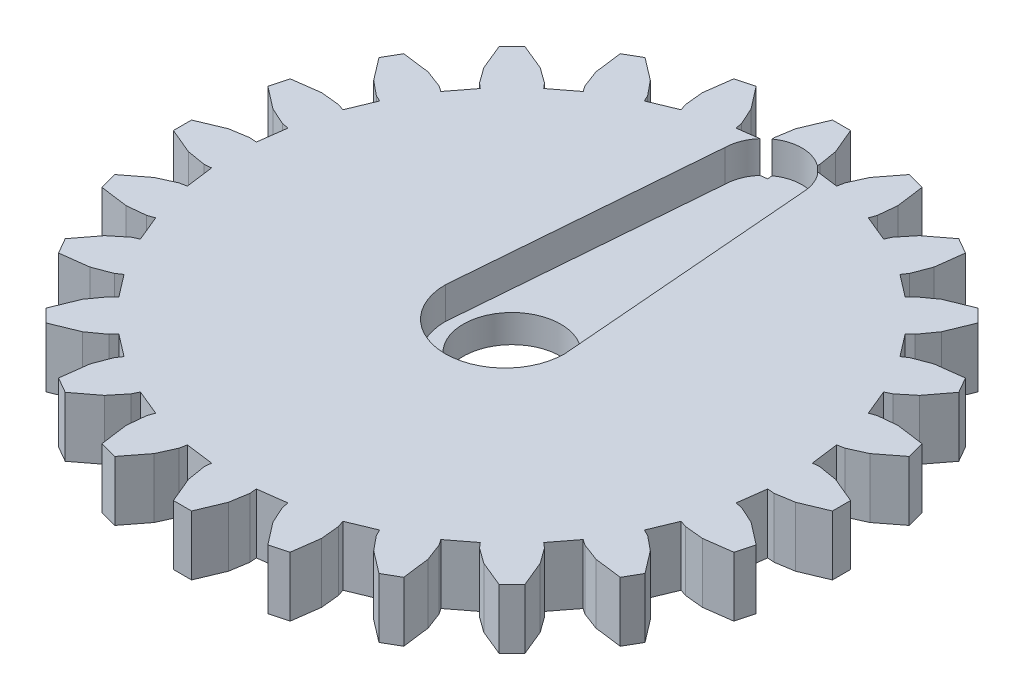
SolidWorks part; units mm, degrees
ref_plane "Front Plane" through (0, 0, 0) normal (0, 0, 1) x (1, 0, 0)
ref_plane "Top Plane" through (0, 0, 0) normal (0, 1, 0) x (1, 0, 0)
ref_plane "Right Plane" through (0, 0, 0) normal (1, 0, 0) x (0, 0, -1)
sketch "Sketch1" plane through (0, 0, 0) normal (0, 1, 0) x (1, 0, 0)
  line L0 (13.9714, 1.4647) -> (14.3221, 1.493)
  line L1 (14.3221, 1.493) -> (15.2571, 1.3398)
  line L2 (15.2571, 1.3398) -> (16.5568, 0.796)
  line L3 (16.5568, 0.796) -> (16.5568, -0.1149)
  line L4 (16.5568, -0.1149) -> (15.2571, -0.6588)
  line L5 (15.2571, -0.6588) -> (14.3221, -0.8119)
  line L6 (14.3221, -0.8119) -> (13.9714, -0.7837)
  line L7 (13.9714, -0.7837) -> (13.7867, -2.1868)
  line L8 (13.7867, -2.1868) -> (14.1327, -2.2503)
  line L9 (14.1327, -2.2503) -> (14.9963, -2.6402)
  line L10 (14.9963, -2.6402) -> (16.1109, -3.5019)
  line L11 (16.1109, -3.5019) -> (15.8751, -4.3818)
  line L12 (15.8751, -4.3818) -> (14.479, -4.5707)
  line L13 (14.479, -4.5707) -> (13.5362, -4.4766)
  line L14 (13.5362, -4.4766) -> (13.2048, -4.3586)
  line L15 (13.2048, -4.3586) -> (12.6632, -5.6661)
  line L16 (12.6632, -5.6661) -> (12.981, -5.817)
  line L17 (12.981, -5.817) -> (13.7142, -6.4171)
  line L18 (13.7142, -6.4171) -> (14.5678, -7.5379)
  line L19 (14.5678, -7.5379) -> (14.1123, -8.3268)
  line L20 (14.1123, -8.3268) -> (12.7149, -8.148)
  line L21 (12.7149, -8.148) -> (11.8285, -7.8131)
  line L22 (11.8285, -7.8131) -> (11.539, -7.6133)
  line L23 (11.539, -7.6133) -> (10.6774, -8.7361)
  line L24 (10.6774, -8.7361) -> (10.9454, -8.9641)
  line L25 (10.9454, -8.9641) -> (11.4982, -9.7335)
  line L26 (11.4982, -9.7335) -> (12.0327, -11.0371)
  line L27 (12.0327, -11.0371) -> (11.3886, -11.6812)
  line L28 (11.3886, -11.6812) -> (10.085, -11.1467)
  line L29 (10.085, -11.1467) -> (9.3156, -10.5939)
  line L30 (9.3156, -10.5939) -> (9.0876, -10.3259)
  line L31 (9.0876, -10.3259) -> (7.9648, -11.1875)
  line L32 (7.9648, -11.1875) -> (8.1646, -11.477)
  line L33 (8.1646, -11.477) -> (8.4995, -12.3634)
  line L34 (8.4995, -12.3634) -> (8.6783, -13.7608)
  line L35 (8.6783, -13.7608) -> (7.8894, -14.2163)
  line L36 (7.8894, -14.2163) -> (6.7686, -13.3627)
  line L37 (6.7686, -13.3627) -> (6.1685, -12.6295)
  line L38 (6.1685, -12.6295) -> (6.0176, -12.3117)
  line L39 (6.0176, -12.3117) -> (4.7101, -12.8533)
  line L40 (4.7101, -12.8533) -> (4.8281, -13.1847)
  line L41 (4.8281, -13.1847) -> (4.9222, -14.1275)
  line L42 (4.9222, -14.1275) -> (4.7333, -15.5236)
  line L43 (4.7333, -15.5236) -> (3.8534, -15.7594)
  line L44 (3.8534, -15.7594) -> (2.9917, -14.6448)
  line L45 (2.9917, -14.6448) -> (2.6018, -13.7812)
  line L46 (2.6018, -13.7812) -> (2.5383, -13.4352)
  line L47 (2.5383, -13.4352) -> (1.1352, -13.6199)
  line L48 (1.1352, -13.6199) -> (1.1634, -13.9706)
  line L49 (1.1634, -13.9706) -> (1.0103, -14.9056)
  line L50 (1.0103, -14.9056) -> (0.4664, -16.2053)
  line L51 (0.4664, -16.2053) -> (-0.4445, -16.2053)
  line L52 (-0.4445, -16.2053) -> (-0.9883, -14.9056)
  line L53 (-0.9883, -14.9056) -> (-1.1415, -13.9706)
  line L54 (-1.1415, -13.9706) -> (-1.1132, -13.6199)
  line L55 (-1.1132, -13.6199) -> (-2.5164, -13.4352)
  line L56 (-2.5164, -13.4352) -> (-2.5799, -13.7812)
  line L57 (-2.5799, -13.7812) -> (-2.9698, -14.6448)
  line L58 (-2.9698, -14.6448) -> (-3.8315, -15.7594)
  line L59 (-3.8315, -15.7594) -> (-4.7114, -15.5236)
  line L60 (-4.7114, -15.5236) -> (-4.9003, -14.1275)
  line L61 (-4.9003, -14.1275) -> (-4.8062, -13.1847)
  line L62 (-4.8062, -13.1847) -> (-4.6882, -12.8533)
  line L63 (-4.6882, -12.8533) -> (-5.9957, -12.3117)
  line L64 (-5.9957, -12.3117) -> (-6.1466, -12.6295)
  line L65 (-6.1466, -12.6295) -> (-6.7467, -13.3627)
  line L66 (-6.7467, -13.3627) -> (-7.8675, -14.2163)
  line L67 (-7.8675, -14.2163) -> (-8.6564, -13.7608)
  line L68 (-8.6564, -13.7608) -> (-8.4775, -12.3634)
  line L69 (-8.4775, -12.3634) -> (-8.1426, -11.477)
  line L70 (-8.1426, -11.477) -> (-7.9428, -11.1875)
  line L71 (-7.9428, -11.1875) -> (-9.0656, -10.3259)
  line L72 (-9.0656, -10.3259) -> (-9.2936, -10.5939)
  line L73 (-9.2936, -10.5939) -> (-10.0631, -11.1467)
  line L74 (-10.0631, -11.1467) -> (-11.3666, -11.6812)
  line L75 (-11.3666, -11.6812) -> (-12.0108, -11.0371)
  line L76 (-12.0108, -11.0371) -> (-11.4763, -9.7335)
  line L77 (-11.4763, -9.7335) -> (-10.9234, -8.9641)
  line L78 (-10.9234, -8.9641) -> (-10.6555, -8.7361)
  line L79 (-10.6555, -8.7361) -> (-11.517, -7.6133)
  line L80 (-11.517, -7.6133) -> (-11.8066, -7.8131)
  line L81 (-11.8066, -7.8131) -> (-12.693, -8.148)
  line L82 (-12.693, -8.148) -> (-14.0904, -8.3268)
  line L83 (-14.0904, -8.3268) -> (-14.5459, -7.5379)
  line L84 (-14.5459, -7.5379) -> (-13.6922, -6.4171)
  line L85 (-13.6922, -6.4171) -> (-12.959, -5.817)
  line L86 (-12.959, -5.817) -> (-12.6412, -5.6661)
  line L87 (-12.6412, -5.6661) -> (-13.1828, -4.3586)
  line L88 (-13.1828, -4.3586) -> (-13.5142, -4.4766)
  line L89 (-13.5142, -4.4766) -> (-14.4571, -4.5707)
  line L90 (-14.4571, -4.5707) -> (-15.8532, -4.3818)
  line L91 (-15.8532, -4.3818) -> (-16.089, -3.5019)
  line L92 (-16.089, -3.5019) -> (-14.9743, -2.6402)
  line L93 (-14.9743, -2.6402) -> (-14.1108, -2.2503)
  line L94 (-14.1108, -2.2503) -> (-13.7648, -2.1868)
  line L95 (-13.7648, -2.1868) -> (-13.9495, -0.7837)
  line L96 (-13.9495, -0.7837) -> (-14.3002, -0.8119)
  line L97 (-14.3002, -0.8119) -> (-15.2352, -0.6588)
  line L98 (-15.2352, -0.6588) -> (-16.5349, -0.1149)
  line L99 (-16.5349, -0.1149) -> (-16.5349, 0.796)
  line L100 (-16.5349, 0.796) -> (-15.2352, 1.3398)
  line L101 (-15.2352, 1.3398) -> (-14.3002, 1.493)
  line L102 (-14.3002, 1.493) -> (-13.9495, 1.4647)
  line L103 (-13.9495, 1.4647) -> (-13.7648, 2.8679)
  line L104 (-13.7648, 2.8679) -> (-14.1108, 2.9314)
  line L105 (-14.1108, 2.9314) -> (-14.9743, 3.3213)
  line L106 (-14.9743, 3.3213) -> (-16.089, 4.183)
  line L107 (-16.089, 4.183) -> (-15.8532, 5.0629)
  line L108 (-15.8532, 5.0629) -> (-14.4571, 5.2518)
  line L109 (-14.4571, 5.2518) -> (-13.5142, 5.1577)
  line L110 (-13.5142, 5.1577) -> (-13.1828, 5.0397)
  line L111 (-13.1828, 5.0397) -> (-12.6412, 6.3472)
  line L112 (-12.6412, 6.3472) -> (-12.959, 6.4981)
  line L113 (-12.959, 6.4981) -> (-13.6922, 7.0982)
  line L114 (-13.6922, 7.0982) -> (-14.5459, 8.219)
  line L115 (-14.5459, 8.219) -> (-14.0904, 9.0079)
  line L116 (-14.0904, 9.0079) -> (-12.693, 8.829)
  line L117 (-12.693, 8.829) -> (-11.8066, 8.4941)
  line L118 (-11.8066, 8.4941) -> (-11.517, 8.2943)
  line L119 (-11.517, 8.2943) -> (-10.6555, 9.4171)
  line L120 (-10.6555, 9.4171) -> (-10.9234, 9.6451)
  line L121 (-10.9234, 9.6451) -> (-11.4763, 10.4146)
  line L122 (-11.4763, 10.4146) -> (-12.0108, 11.7181)
  line L123 (-12.0108, 11.7181) -> (-11.3666, 12.3623)
  line L124 (-11.3666, 12.3623) -> (-10.0631, 11.8278)
  line L125 (-10.0631, 11.8278) -> (-9.2936, 11.2749)
  line L126 (-9.2936, 11.2749) -> (-9.0656, 11.007)
  line L127 (-9.0656, 11.007) -> (-7.9428, 11.8685)
  line L128 (-7.9428, 11.8685) -> (-8.1426, 12.1581)
  line L129 (-8.1426, 12.1581) -> (-8.4775, 13.0445)
  line L130 (-8.4775, 13.0445) -> (-8.6564, 14.4419)
  line L131 (-8.6564, 14.4419) -> (-7.8675, 14.8974)
  line L132 (-7.8675, 14.8974) -> (-6.7467, 14.0437)
  line L133 (-6.7467, 14.0437) -> (-6.1466, 13.3105)
  line L134 (-6.1466, 13.3105) -> (-5.9957, 12.9927)
  line L135 (-5.9957, 12.9927) -> (-4.6882, 13.5343)
  line L136 (-4.6882, 13.5343) -> (-4.8062, 13.8657)
  line L137 (-4.8062, 13.8657) -> (-4.9003, 14.8086)
  line L138 (-4.9003, 14.8086) -> (-4.7114, 16.2047)
  line L139 (-4.7114, 16.2047) -> (-3.8315, 16.4405)
  line L140 (-3.8315, 16.4405) -> (-2.9698, 15.3258)
  line L141 (-2.9698, 15.3258) -> (-2.5799, 14.4623)
  line L142 (-2.5799, 14.4623) -> (-2.5164, 14.1163)
  line L143 (-2.5164, 14.1163) -> (-1.1132, 14.301)
  line L144 (-1.1132, 14.301) -> (-1.1415, 14.6517)
  line L145 (-1.1415, 14.6517) -> (-0.9883, 15.5867)
  line L146 (-0.9883, 15.5867) -> (-0.4445, 16.8864)
  line L147 (-0.4445, 16.8864) -> (0.4664, 16.8864)
  line L148 (0.4664, 16.8864) -> (1.0103, 15.5867)
  line L149 (1.0103, 15.5867) -> (1.1634, 14.6517)
  line L150 (1.1634, 14.6517) -> (1.1352, 14.301)
  line L151 (1.1352, 14.301) -> (2.5383, 14.1163)
  line L152 (2.5383, 14.1163) -> (2.6018, 14.4623)
  line L153 (2.6018, 14.4623) -> (2.9917, 15.3258)
  line L154 (2.9917, 15.3258) -> (3.8534, 16.4405)
  line L155 (3.8534, 16.4405) -> (4.7333, 16.2047)
  line L156 (4.7333, 16.2047) -> (4.9222, 14.8086)
  line L157 (4.9222, 14.8086) -> (4.8281, 13.8657)
  line L158 (4.8281, 13.8657) -> (4.7101, 13.5343)
  line L159 (4.7101, 13.5343) -> (6.0176, 12.9927)
  line L160 (6.0176, 12.9927) -> (6.1685, 13.3105)
  line L161 (6.1685, 13.3105) -> (6.7686, 14.0437)
  line L162 (6.7686, 14.0437) -> (7.8894, 14.8974)
  line L163 (7.8894, 14.8974) -> (8.6783, 14.4419)
  line L164 (8.6783, 14.4419) -> (8.4995, 13.0445)
  line L165 (8.4995, 13.0445) -> (8.1646, 12.1581)
  line L166 (8.1646, 12.1581) -> (7.9648, 11.8685)
  line L167 (7.9648, 11.8685) -> (9.0876, 11.007)
  line L168 (9.0876, 11.007) -> (9.3156, 11.2749)
  line L169 (9.3156, 11.2749) -> (10.085, 11.8278)
  line L170 (10.085, 11.8278) -> (11.3886, 12.3623)
  line L171 (11.3886, 12.3623) -> (12.0327, 11.7181)
  line L172 (12.0327, 11.7181) -> (11.4982, 10.4146)
  line L173 (11.4982, 10.4146) -> (10.9454, 9.6451)
  line L174 (10.9454, 9.6451) -> (10.6774, 9.4171)
  line L175 (10.6774, 9.4171) -> (11.539, 8.2943)
  line L176 (11.539, 8.2943) -> (11.8285, 8.4941)
  line L177 (11.8285, 8.4941) -> (12.7149, 8.829)
  line L178 (12.7149, 8.829) -> (14.1123, 9.0079)
  line L179 (14.1123, 9.0079) -> (14.5678, 8.219)
  line L180 (14.5678, 8.219) -> (13.7142, 7.0982)
  line L181 (13.7142, 7.0982) -> (12.981, 6.4981)
  line L182 (12.981, 6.4981) -> (12.6632, 6.3472)
  line L183 (12.6632, 6.3472) -> (13.2048, 5.0397)
  line L184 (13.2048, 5.0397) -> (13.5362, 5.1577)
  line L185 (13.5362, 5.1577) -> (14.479, 5.2518)
  line L186 (14.479, 5.2518) -> (15.8751, 5.0629)
  line L187 (15.8751, 5.0629) -> (16.1109, 4.183)
  line L188 (16.1109, 4.183) -> (14.9963, 3.3213)
  line L189 (14.9963, 3.3213) -> (14.1327, 2.9314)
  line L190 (14.1327, 2.9314) -> (13.7867, 2.8679)
  line L191 (13.7867, 2.8679) -> (13.9714, 1.4647)
  line L192 (-13.8571, 2.1663) -> (13.879, -1.4852) construction
  circle A1 centre (0.011, 0.3405) radius 2.45
  point P198 (-13.8571, 2.1663)
  point P199 (13.879, -1.4852)
  dimension "D1" = 4.9
  dimension "D2" = 27.9755
extrude "Boss-Extrude1" add sketch "Sketch1" along normal blind 3
sketch "Sketch2" plane through (0, 3, 0) normal (0, 1, 0) x (1, 0, 0)
  line L0 (0, 0) -> (0, 12.9584) construction
  line L1 (-3, 0) -> (-1.95, 13)
  line L2 (3, 0) -> (1.95, 13)
  arc A0 (-3, 0) -> (3, 0) centre (0, 0) ccw
  arc A1 (-1.95, 13) -> (1.95, 13) centre (0, 12.9584) cw
  point P6 (0, 14.9089)
extrude "Cut-Extrude1" cut sketch "Sketch2" against normal blind 1.6
